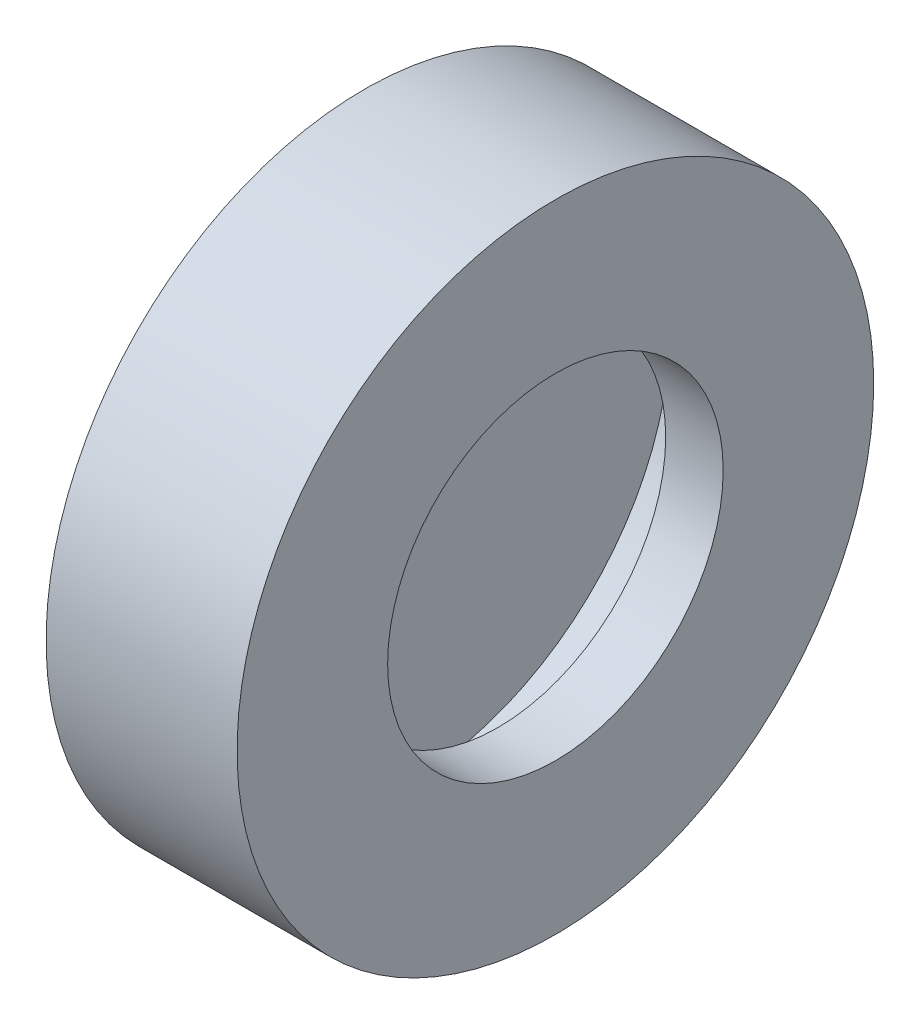
SolidWorks part; units mm, degrees
ref_plane "Front Plane" through (0, 0, 0) normal (0, 0, 1) x (1, 0, 0)
ref_plane "Top Plane" through (0, 0, 0) normal (0, 1, 0) x (1, 0, 0)
ref_plane "Right Plane" through (0, 0, 0) normal (1, 0, 0) x (0, 0, -1)
sketch "Sketch1" plane through (0, 0, 0) normal (1, 0, 0) x (0, 0, -1)
  circle A0 centre (0, 0) radius 5
  dimension "D1" = 10
extrude "Boss-Extrude1" add sketch "Sketch1" along normal blind 3
sketch "Sketch2" plane through (0, 0, 0) normal (0, 1, 0) x (1, 0, 0)
  line L0 (3, 2.6354) -> (2.097, 2.6354)
  line L1 (3, -5) -> (3, 5) construction
  line L2 (2.097, 2.6354) -> (2.097, 4.1364)
  line L3 (2.097, 4.1364) -> (0.6642, 4.1364)
  line L4 (3, 2.6354) -> (3.6151, 2.6354)
  line L5 (3.6151, 0) -> (3.6151, 2.6354)
  line L10 (3.6151, 0) -> (0.6642, 0)
  line L11 (0.6642, 0) -> (0.6642, 4.1364)
revolve "Cut-Revolve1" cut sketch "Sketch2" angle 360 about L10
